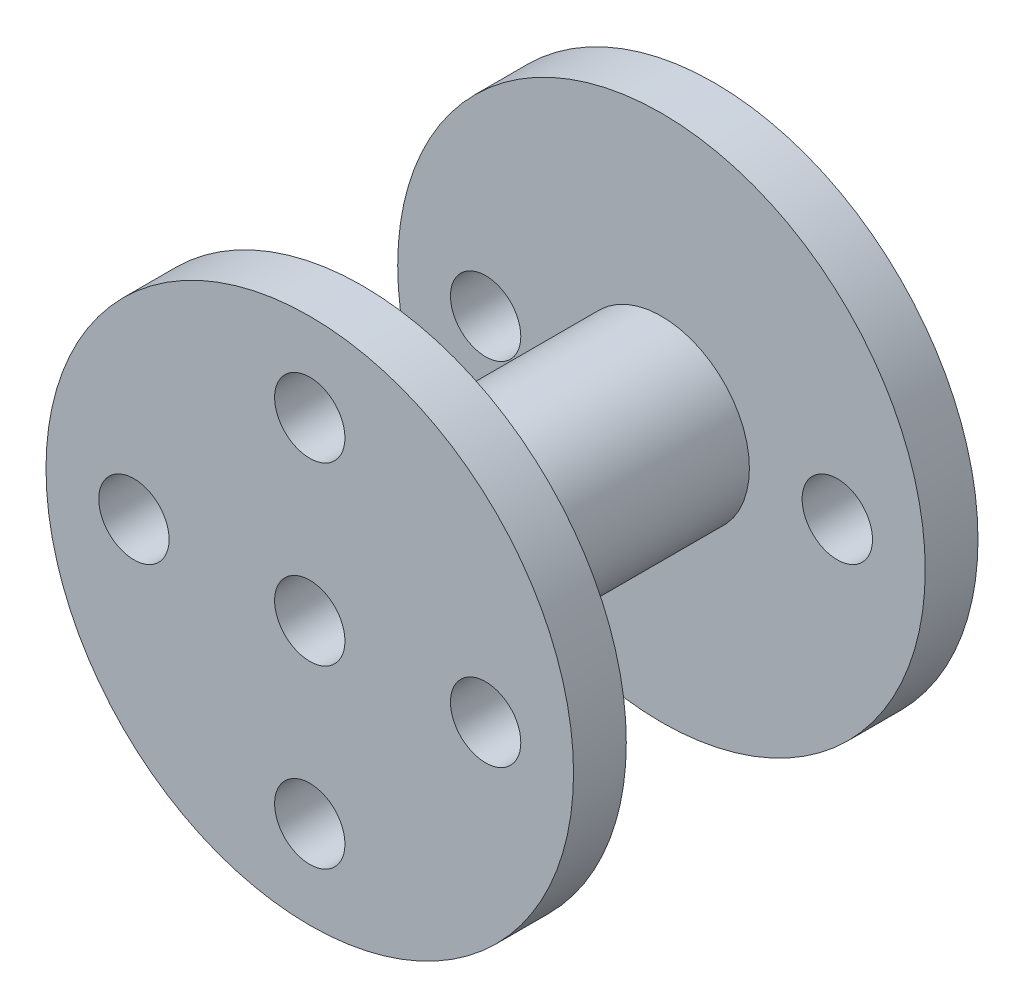
SolidWorks part; units mm, degrees
ref_plane "Front" through (0, 0, 0) normal (0, 0, 1) x (1, 0, 0)
ref_plane "Top" through (0, 0, 0) normal (0, 1, 0) x (1, 0, 0)
ref_plane "Right" through (0, 0, 0) normal (1, 0, 0) x (0, 0, -1)
sketch "草图1" plane through (0, 0, 0) normal (0, 0, 1) x (1, 0, 0)
  line L0 (0, 0) -> (10, 0) construction
  line L1 (0, 0) -> (-10, 0) construction
  circle A0 centre (0, 0) radius 15
  circle A2 centre (10, 0) radius 2
  circle A3 centre (-10, 0) radius 2
  dimension "D1" = 30
  dimension "D2" = 4
  dimension "D3" = 10
  dimension "D4" = 10
extrude "凸台-拉伸2" add sketch "草图1" along normal blind 3
sketch "草图2" plane through (0, 0, 3) normal (0, 0, 1) x (1, 0, 0)
  circle A0 centre (0, 0) radius 5
  dimension "D1" = 10
extrude "凸台-拉伸3" add sketch "草图2" along normal blind 17
sketch "草图4" plane through (0, 0, 20) normal (0, 0, 1) x (1, 0, 0)
  line L0 (0, 0) -> (-10, 0) construction
  circle A0 centre (0, 0) radius 15
  circle A1 centre (-10, 0) radius 2
  circle A2 centre (0, 10) radius 2
  circle A3 centre (10, 0) radius 2
  circle A4 centre (0, -10) radius 2
  point P14 (0, 0)
  dimension "D1" = 4
extrude "凸台-拉伸4" add sketch "草图4" along normal blind 3
sketch "草图8" plane through (0, 0, 23) normal (0, 0, 1) x (1, 0, 0)
  circle A0 centre (0, 0) radius 2
extrude "切除-拉伸2" cut sketch "草图8" against normal blind 15
